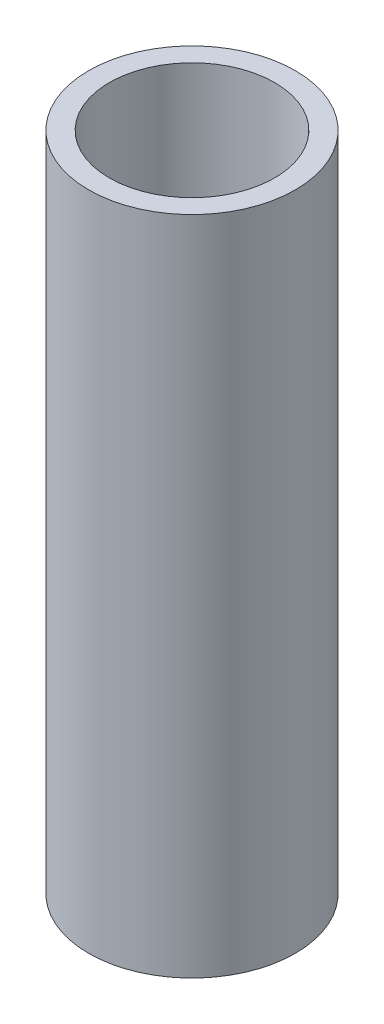
SolidWorks part; units mm, degrees
ref_plane "Front Plane" through (0, 0, 0) normal (0, 0, 1) x (1, 0, 0)
ref_plane "Top Plane" through (0, 0, 0) normal (0, 1, 0) x (1, 0, 0)
ref_plane "Right Plane" through (0, 0, 0) normal (1, 0, 0) x (0, 0, -1)
sketch "Sketch2" plane through (0, 0, 0) normal (0, 1, 0) x (1, 0, 0)
  circle A0 centre (0, 0) radius 20
  circle A1 centre (0, 0) radius 13.5
extrude "Boss-Extrude1" add sketch "Sketch2" along normal blind 128
sketch "Sketch3" plane through (0, 128, 0) normal (0, 1, 0) x (1, 0, 0)
  circle A0 centre (0, 0) radius 16
extrude "Cut-Extrude1" cut sketch "Sketch3" against normal blind 28
